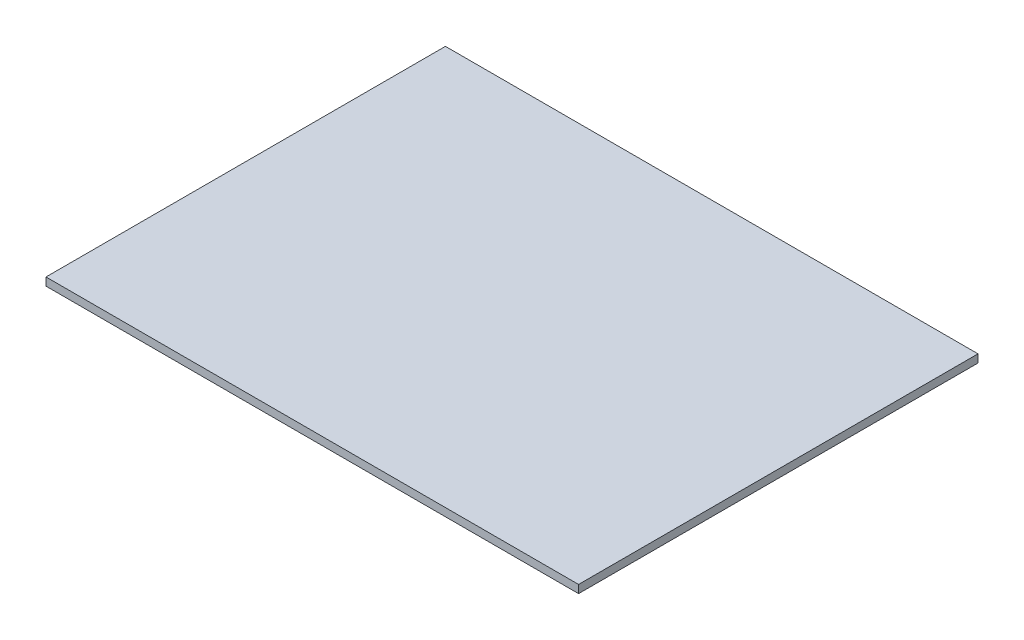
SolidWorks part; units mm, degrees
ref_plane "Plan de face" through (0, 0, 0) normal (0, 0, 1) x (1, 0, 0)
ref_plane "Plan de dessus" through (0, 0, 0) normal (0, 1, 0) x (1, 0, 0)
ref_plane "Plan de droite" through (0, 0, 0) normal (1, 0, 0) x (0, 0, -1)
sketch "Esquisse2" plane through (0, 0, 0) normal (0, 1, 0) x (1, 0, 0)
  line L1 (0, 0) -> (200, 0)
  line L2 (0, 0) -> (0, 150)
  line L3 (0, 150) -> (200, 150)
  line L4 (200, 0) -> (200, 150)
  dimension "D1" = 150
  dimension "D2" = 200
extrude "Boss.-Extru.1" add sketch "Esquisse2" along normal blind 3
